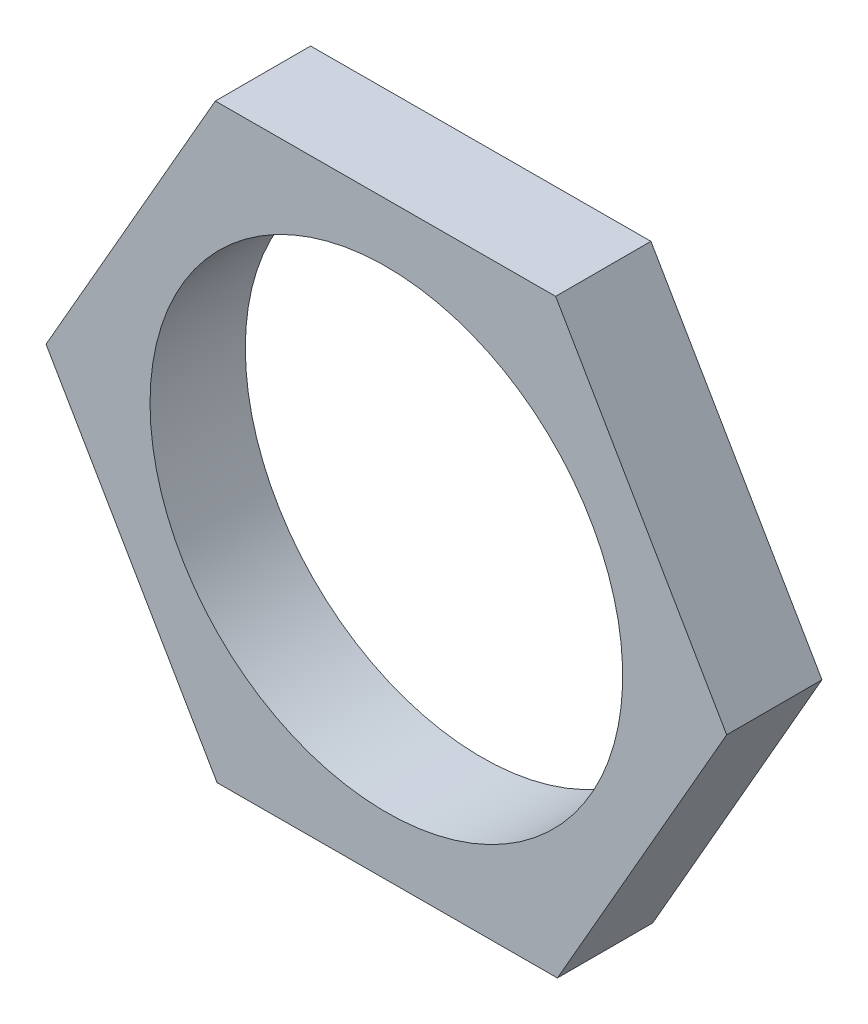
SolidWorks part; units mm, degrees
material "Latão"
ref_plane "Plano frontal" through (0, 0, 0) normal (0, 0, 1) x (1, 0, 0)
ref_plane "Plano superior" through (0, 0, 0) normal (0, 1, 0) x (1, 0, 0)
ref_plane "Plano direito" through (0, 0, 0) normal (1, 0, 0) x (0, 0, -1)
sketch "Esboço1" plane through (0, 0, 0) normal (0, 0, 1) x (1, 0, 0)
  line L1 (3.5535, 6.1973) -> (-3.5903, 6.176)
  line L2 (-3.5903, 6.176) -> (-7.1437, -0.0213)
  line L3 (-7.1437, -0.0213) -> (-3.5535, -6.1973)
  line L4 (-3.5535, -6.1973) -> (3.5903, -6.176)
  line L5 (3.5903, -6.176) -> (7.1437, 0.0213)
  line L6 (7.1437, 0.0213) -> (3.5535, 6.1973)
  circle A0 centre (0, 0) radius 7.1438 construction
  dimension "D1" = 14.2875
extrude "Ressalto-extrusão1" add sketch "Esboço1" along normal blind 2
sketch "Esboço2" plane through (0, 0, 0) normal (0, 0, -1) x (-1, 0, 0)
  circle A0 centre (0, 0) radius 4.9609
  dimension "D1" = 9.9219
extrude "Corte-extrusão1" cut sketch "Esboço2" against normal through all
cosmetic thread "Representação de rosca1" parameters "D2"=11.1125
